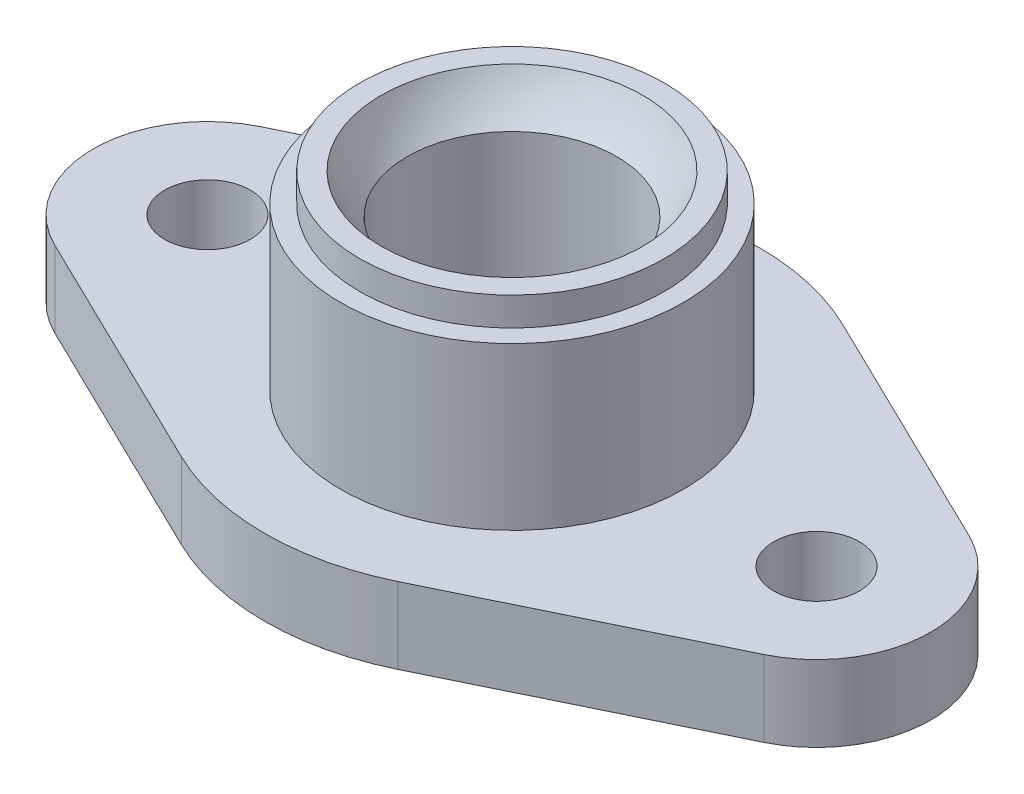
SolidWorks part; units mm, degrees
ref_plane "前视基准面" through (0, 0, 0) normal (0, 0, 1) x (1, 0, 0)
ref_plane "上视基准面" through (0, 0, 0) normal (0, 1, 0) x (1, 0, 0)
ref_plane "右视基准面" through (0, 0, 0) normal (1, 0, 0) x (0, 0, -1)
other "Configuration Table"
sketch "草图1" plane through (0, 0, 0) normal (0, 1, 0) x (1, 0, 0)
  line L0 (0, 0) -> (0, 43.5332) construction
  line L1 (-37.25, 10.7906) -> (-11.375, 23.3797)
  line L2 (37.25, 10.7906) -> (11.375, 23.3797)
  line L3 (20, 0) -> (66.1158, 0) construction
  line L4 (-37.25, -10.7906) -> (-11.375, -23.3797)
  line L5 (37.25, -10.7906) -> (11.375, -23.3797)
  arc A0 (-11.375, -23.3797) -> (11.375, -23.3797) centre (0, 0) ccw
  arc A1 (-37.25, 10.7906) -> (-37.25, -10.7906) centre (-32, 0) ccw
  arc A3 (37.25, 10.7906) -> (37.25, -10.7906) centre (32, 0) cw
  circle A4 centre (-32, 0) radius 4.5
  circle A5 centre (32, 0) radius 4.5
  arc A6 (11.375, 23.3797) -> (-11.375, 23.3797) centre (0, 0) ccw
  circle A7 centre (0, 0) radius 11
  dimension "D1" = 52
  dimension "D3" = 9
  dimension "D4" = 24
  dimension "D5" = 9
  dimension "D6" = 22
  dimension "D2" = 64
extrude "凸台-拉伸1" add sketch "草图1" along normal blind 8
sketch "草图2" plane through (0, 0, 0) normal (1, 0, 0) x (0, 0, -1)
  line L0 (-18, 8) -> (-11, 8)
  line L2 (-23.3797, 8) -> (-10.7906, 8) construction
  line L3 (-18, 8) -> (-18, 25)
  line L4 (-18, 25) -> (-16, 25)
  line L5 (-16, 25) -> (-16, 28)
  line L6 (-11, 8) -> (-11, 0) construction
  line L7 (-11, 8) -> (-11, 23.802)
  line L8 (-13.7477, 28) -> (-16, 28)
  line L9 (0, 0) -> (0, 34) construction
  arc A0 (-13.7477, 28) -> (-11, 23.802) centre (0, 34) ccw
  dimension "D5" = 30
  dimension "D1" = 17
  dimension "D2" = 2
  dimension "D3" = 3
  dimension "D4" = 34
revolve "旋转1" add sketch "草图2" angle 360 about L9
chamfer "倒角1" distance 1.5 angle 45 1 edges at (0, 0, 11)
